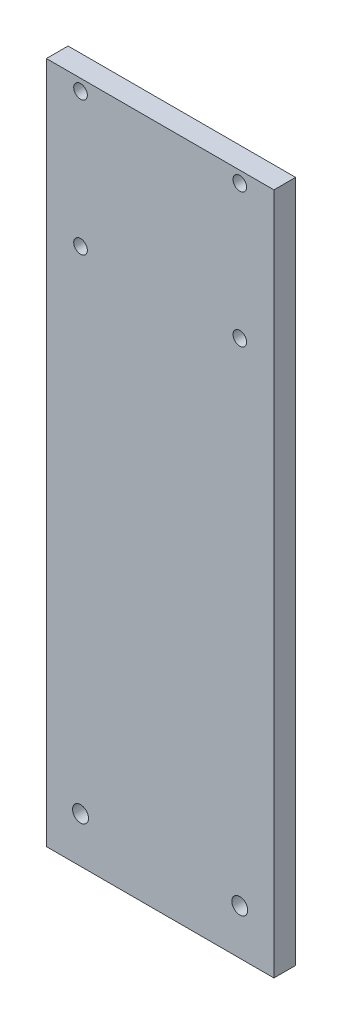
SolidWorks part; units mm, degrees
material "6061 Alloy"
ref_plane "Front Plane" through (0, 0, 0) normal (0, 0, 1) x (1, 0, 0)
ref_plane "Top Plane" through (0, 0, 0) normal (0, 1, 0) x (1, 0, 0)
ref_plane "Right Plane" through (0, 0, 0) normal (1, 0, 0) x (0, 0, -1)
sketch "Sketch1" plane through (0, 0, 0) normal (0, 0, 1) x (1, 0, 0)
  line L0 (22.6357, 113.0124) -> (22.6357, -186.9876) construction
  line L1 (-27.3643, 113.0124) -> (72.6357, 113.0124)
  line L2 (-27.3643, 113.0124) -> (-27.3643, 7.7875)
  line L3 (-27.3643, -186.9876) -> (72.6357, -186.9876)
  line L4 (72.6357, 113.0124) -> (72.6357, 7.7875)
  line L5 (-27.3643, 7.7875) -> (-27.3643, -131.9876)
  line L6 (72.6357, 7.7875) -> (72.6357, -131.9876)
  line L11 (-27.3643, -131.9876) -> (-27.3643, -186.9876)
  line L12 (72.6357, -131.9876) -> (72.6357, -186.9876)
  circle A0 centre (-12.3643, 108.0124) radius 3
  circle A1 centre (57.6357, 49.0124) radius 3
  circle A2 centre (-12.3643, 49.0124) radius 3
  circle A3 centre (57.6357, 108.0124) radius 3
  circle A4 centre (-12.3643, -166.9876) radius 3.5
  circle A5 centre (57.6357, -166.9876) radius 3.5
  dimension "D3" = 64
  dimension "D7" = 7
  dimension "D10" = 6
  dimension "D13" = 6
  dimension "D1" = 300
  dimension "D2" = 100
  dimension "D4" = 15
  dimension "D5" = 15
  dimension "D6" = 5
  dimension "D8" = 20
  dimension "D9" = 15
  dimension "D11" = 280
  dimension "D12" = 85
extrude "Boss-Extrude1" add sketch "Sketch1" along normal blind 9.525
